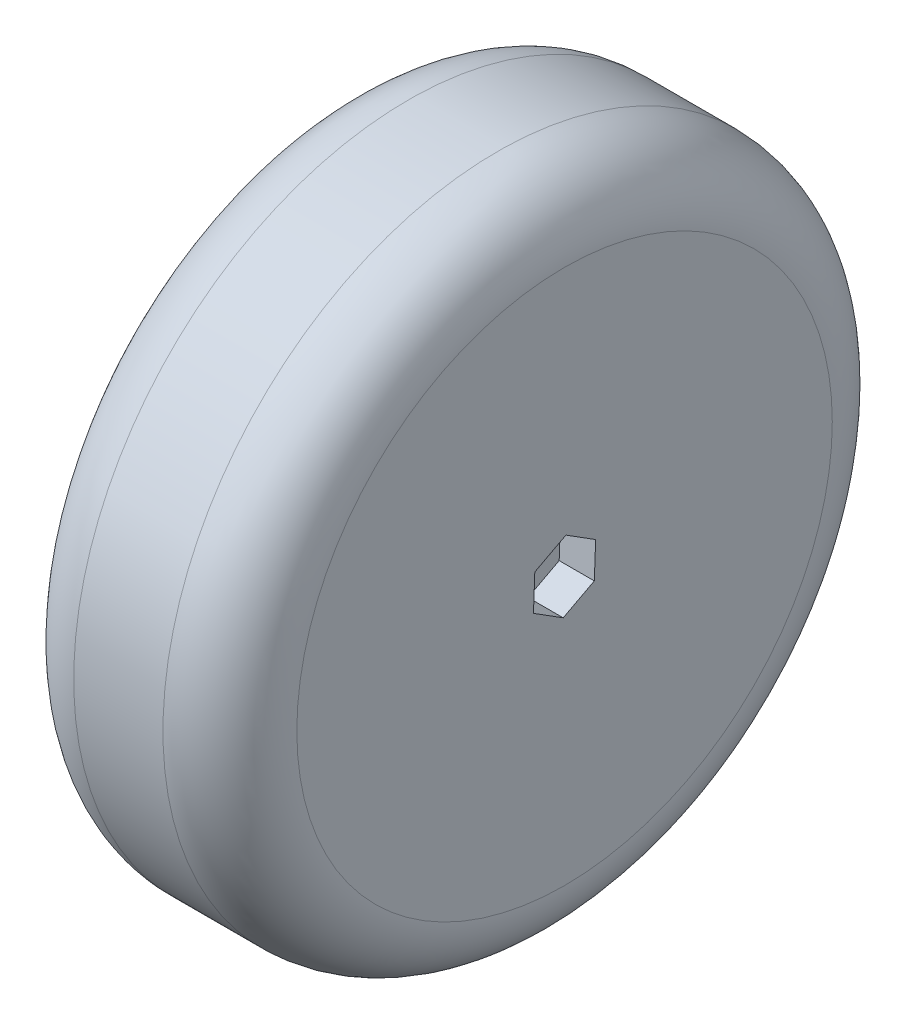
SolidWorks part; units mm, degrees
material "6063-T6"
ref_plane "Front Plane" through (0, 0, 0) normal (0, 0, 1) x (1, 0, 0)
ref_plane "Top Plane" through (0, 0, 0) normal (0, 1, 0) x (1, 0, 0)
ref_plane "Right Plane" through (0, 0, 0) normal (1, 0, 0) x (0, 0, -1)
sketch "Sketch2" plane through (0, 0, 0) normal (1, 0, 0) x (0, 0, -1)
  circle A0 centre (0, 0) radius 38.1
extrude "Boss-Extrude2" add sketch "Sketch2" along normal blind 25.4 contours A0
fillet "Fillet3" radius 7.62 1 edges at (25.4, 0, -38.1)
fillet "Fillet5" radius 7.62 1 edges at (0, 0, -38.1)
sketch "Sketch4" plane through (25.4, 0, 0) normal (1, 0, 0) x (0, 0, -1)
  circle A0 centre (0, 0) radius 1.7
extrude "Cut-Extrude1" cut sketch "Sketch4" against normal blind 25.4
sketch "Sketch5" plane through (25.4, 0, 0) normal (1, 0, 0) x (0, 0, -1)
  line L1 (-3.3873, 2.1327) -> (-3.5406, -1.8671)
  line L2 (-3.5406, -1.8671) -> (-0.1534, -3.9998)
  line L3 (-0.1534, -3.9998) -> (3.3873, -2.1327)
  line L4 (3.3873, -2.1327) -> (3.5406, 1.8671)
  line L5 (3.5406, 1.8671) -> (0.1534, 3.9998)
  line L6 (0.1534, 3.9998) -> (-3.3873, 2.1327)
  circle A0 centre (0, 0) radius 3.4665 construction
extrude "Cut-Extrude2" cut sketch "Sketch5" against normal blind 4
